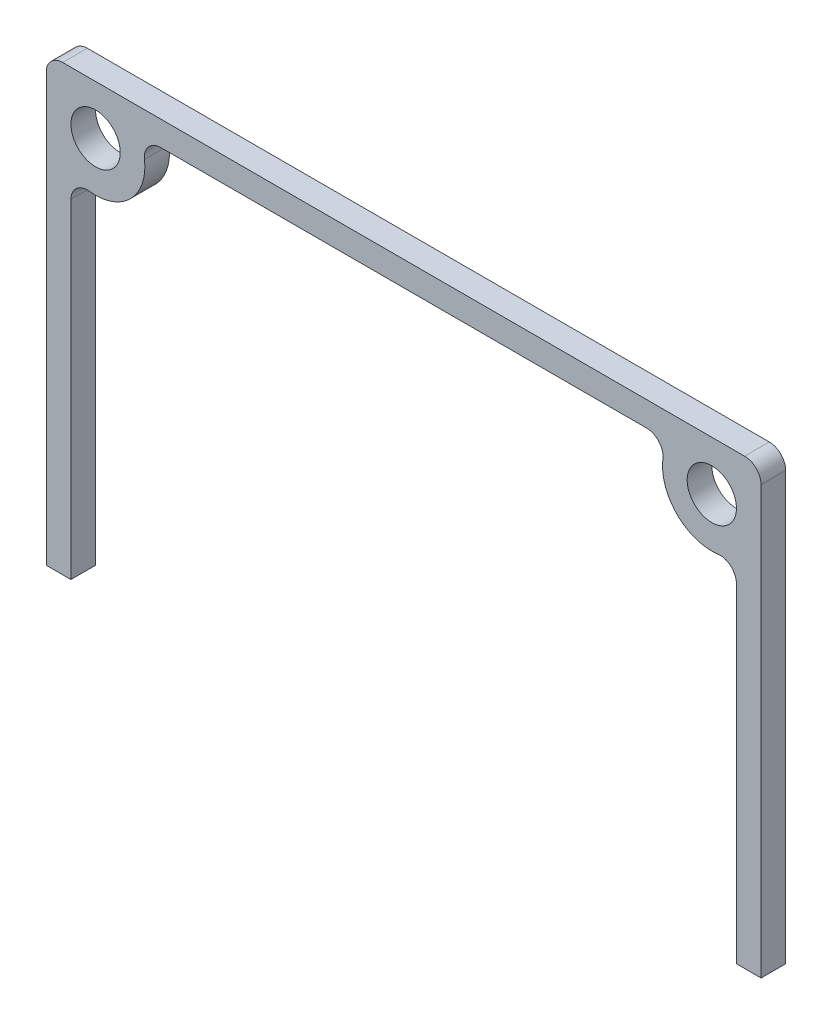
SolidWorks part; units mm, degrees
material "Pine"
ref_plane "Front Plane" through (0, 0, 0) normal (0, 0, 1) x (1, 0, 0)
ref_plane "Top Plane" through (0, 0, 0) normal (0, 1, 0) x (1, 0, 0)
ref_plane "Right Plane" through (0, 0, 0) normal (1, 0, 0) x (0, 0, -1)
sketch "Sketch1" plane through (0, 0, 0) normal (0, 0, 1) x (1, 0, 0)
  line L0 (276.225, 0) -> (276.225, 330.2)
  line L1 (276.225, 0) -> (257.175, 0)
  line L2 (257.175, 0) -> (257.175, 76.2)
  line L3 (276.225, 342.9) -> (-276.225, 342.9) construction
  line L5 (257.175, 76.2) -> (257.175, 165.1) construction
  line L7 (0, 342.9) -> (0, 0) construction
  line L8 (0, 76.2) -> (276.225, 76.2) construction
  line L11 (257.175, 165.1) -> (257.175, 342.9) construction
  line L12 (257.175, 165.1) -> (257.175, 76.2)
  line L19 (187.7234, 323.85) -> (-187.7234, 323.85)
  line L20 (263.525, 342.9) -> (-263.525, 342.9)
  line L21 (257.175, 165.1) -> (257.175, 254.3984)
  line L22 (205.1294, 323.85) -> (257.175, 323.85) construction
  line L23 (-257.175, 165.1) -> (-257.175, 254.3984)
  line L24 (-257.175, 165.1) -> (-257.175, 76.2)
  line L25 (-257.175, 0) -> (-257.175, 76.2)
  line L26 (-276.225, 0) -> (-257.175, 0)
  line L27 (-276.225, 0) -> (-276.225, 330.2)
  arc A12 (242.8875, 266.9988) -> (200.3238, 309.5625) centre (238.125, 304.8) cw
  circle A13 centre (238.125, 304.8) radius 19.05
  arc A14 (263.525, 342.9) -> (276.225, 330.2) centre (263.525, 330.2) cw
  arc A15 (257.175, 254.3984) -> (242.8875, 266.9988) centre (244.475, 254.3984) ccw
  arc A16 (187.7234, 323.85) -> (200.3238, 309.5625) centre (187.7234, 311.15) cw
  circle A17 centre (-238.125, 304.8) radius 19.05
  arc A18 (-187.7234, 323.85) -> (-200.3238, 309.5625) centre (-187.7234, 311.15) ccw
  arc A19 (-242.8875, 266.9988) -> (-200.3238, 309.5625) centre (-238.125, 304.8) ccw
  arc A20 (-257.175, 254.3984) -> (-242.8875, 266.9988) centre (-244.475, 254.3984) cw
  arc A21 (-263.525, 342.9) -> (-276.225, 330.2) centre (-263.525, 330.2) ccw
  point P1 (181.2586, 319.3213)
  point P16 (0, 342.9)
  point P21 (257.175, 271.8044)
  point P31 (0, 323.85)
  dimension "D6" = 19.05
  dimension "D8" = 38.1
  dimension "D9" = 12.7
  dimension "D1" = 342.9
  dimension "D2" = 19.05
  dimension "D3" = 552.45
  dimension "D4" = 76.2
  dimension "D5" = 19.05
  dimension "D7" = 88.9
extrude "Boss-Extrude1" add sketch "Sketch1" along normal blind 19.05
